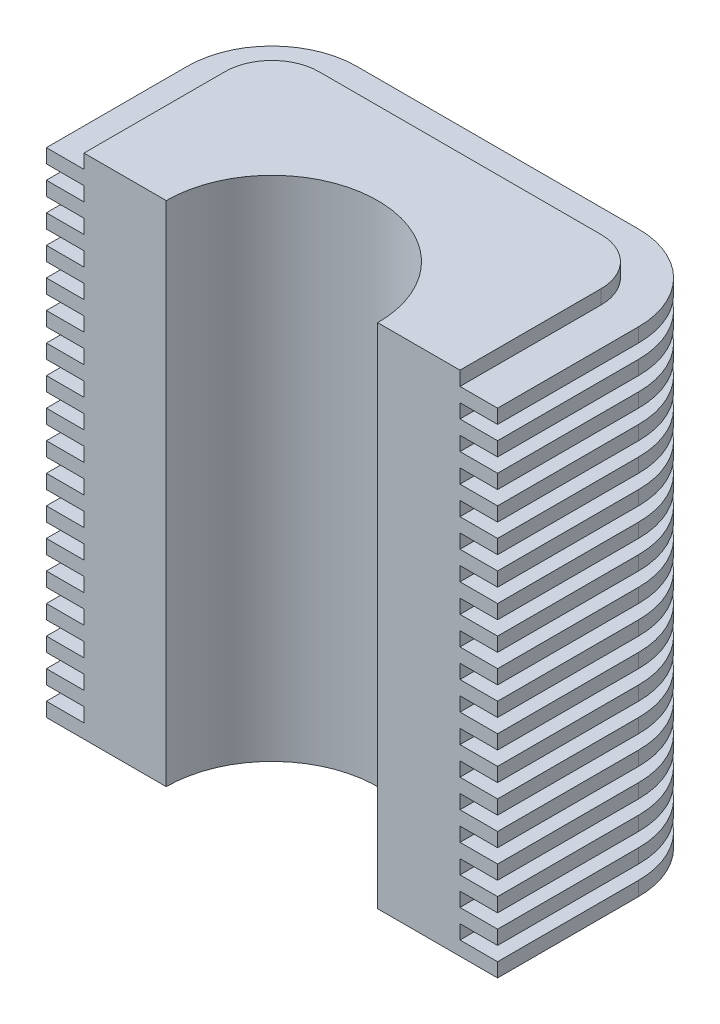
SolidWorks part; units mm, degrees
ref_plane "Płaszczyzna przednia" through (0, 0, 0) normal (0, 0, 1) x (1, 0, 0)
ref_plane "Płaszczyzna górna" through (0, 0, 0) normal (0, 1, 0) x (1, 0, 0)
ref_plane "Płaszczyzna prawa" through (0, 0, 0) normal (1, 0, 0) x (0, 0, -1)
sketch "Szkic1" plane through (0, 0, 0) normal (0, 1, 0) x (1, 0, 0)
  line L0 (40, 0) -> (40, 40)
  line L1 (40, 40) -> (-40, 40)
  line L2 (-40, 40) -> (-40, 0)
  line L3 (-40, 0) -> (-22.5, 0)
  line L4 (22.5, 0) -> (40, 0)
  line L5 (-22.5, 0) -> (22.5, 0) construction
  arc A0 (-22.5, 0) -> (22.5, 0) centre (0, 0) cw
  point P8 (0, 22.5)
  dimension "D1" = 40
  dimension "D2" = 80
  dimension "D3" = 22.5
extrude "Dodanie-wyciągnięcie1" add sketch "Szkic1" along normal blind 108
fillet "Zaokrąglenie1" radius 10 2 edges at (-40, 54, -40) (40, 54, -40)
sketch "Szkic6" plane through (0, 0, 0) normal (0, -1, 0) x (1, 0, 0)
  line L3 (-48, 0) -> (-40, 0)
  line L4 (40, 0) -> (48, 0)
  line L6 (48, 0) -> (48, -30)
  line L7 (-48, -30) -> (-48, 0)
  line L8 (30, -48) -> (-30, -48)
  line L9 (48, 0) -> (48, -30)
  line L10 (-48, -30) -> (-48, 0)
  line L11 (30, -48) -> (-30, -48)
  line L16 (-40, 0) -> (-40, -30)
  line L17 (-30, -40) -> (30, -40)
  line L18 (40, -30) -> (40, 0)
  line L19 (40, 0) -> (22.5, 0)
  line L20 (-22.5, 0) -> (-40, 0)
  line L24 (40, 0) -> (22.5, 0)
  line L25 (-22.5, 0) -> (-40, 0)
  arc A4 (30, -48) -> (48, -30) centre (30, -30) ccw
  arc A5 (-48, -30) -> (-30, -48) centre (-30, -30) ccw
  arc A6 (30, -48) -> (48, -30) centre (30, -30) ccw
  arc A7 (-48, -30) -> (-30, -48) centre (-30, -30) ccw
  arc A9 (-40, -30) -> (-30, -40) centre (-30, -30) ccw
  arc A10 (30, -40) -> (40, -30) centre (30, -30) ccw
  arc A11 (-22.5, 0) -> (22.5, 0) centre (0, 0) ccw
  arc A14 (-22.5, 0) -> (22.5, 0) centre (0, 0) ccw
  dimension "D1" = 8
  dimension "D2" = 0
extrude "Dodanie-wyciągnięcie2" add sketch "Szkic6" against normal blind 3
pattern_linear "Szyk liniowy1" count 18 spacing 6 along (0, 1, 0) of "Dodanie-wyciągnięcie2"
